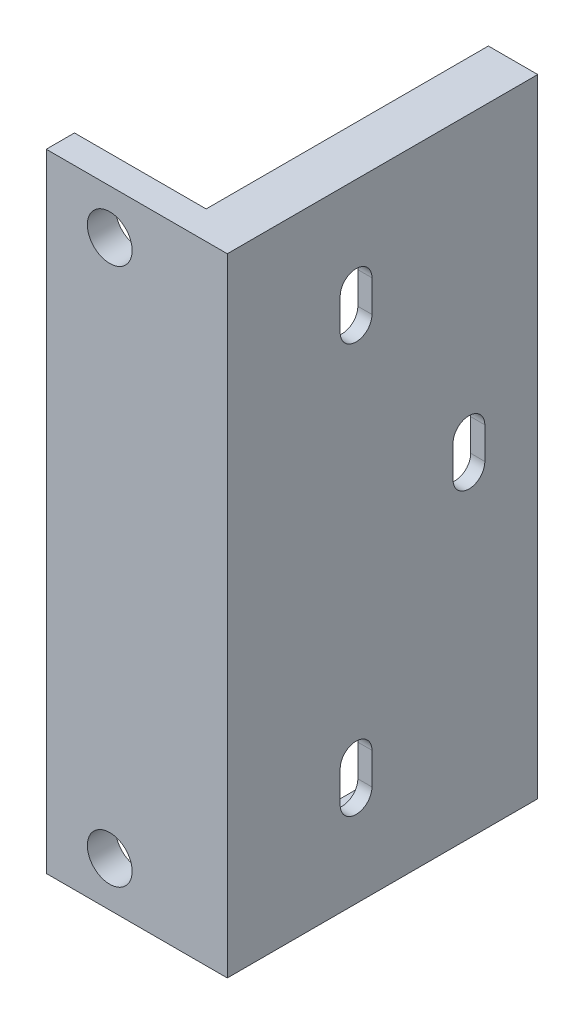
SolidWorks part; units mm, degrees
ref_plane "Front Plane" through (0, 0, 0) normal (0, 0, 1) x (1, 0, 0)
ref_plane "Top Plane" through (0, 0, 0) normal (0, 1, 0) x (1, 0, 0)
ref_plane "Right Plane" through (0, 0, 0) normal (1, 0, 0) x (0, 0, -1)
sketch "Sketch1" plane through (0, 0, 0) normal (0, 0, 1) x (1, 0, 0)
  line L0 (0, 44.45) -> (0, -44.45) construction
  line L1 (-38.7822, -44.45) -> (38.7822, -44.45) construction
  line L2 (-38.7822, -44.45) -> (-38.7822, 44.45) construction
  line L3 (-38.7822, 44.45) -> (38.7822, 44.45) construction
  line L4 (38.7822, -44.45) -> (38.7822, 44.45) construction
  line L5 (-38.7822, -44.45) -> (38.7822, 44.45) construction
  line L6 (-38.7822, 44.45) -> (38.7822, -44.45) construction
  line L7 (0, -44.45) -> (0, 0) construction
  line L8 (0, 0) -> (38.7822, 0) construction
  line L9 (38.7822, 0) -> (-38.7822, 0) construction
  line L10 (-9, 44.45) -> (-9, -44.45)
  line L11 (16.6624, 44.45) -> (16.6624, -44.45) construction
  line L12 (-9, 44.45) -> (38.7822, 44.45) construction
  line L13 (-9, 44.45) -> (-9, -44.45)
  line L14 (-9, -44.45) -> (38.7822, -44.45) construction
  line L15 (38.7822, 44.45) -> (38.7822, -44.45) construction
  line L17 (-9, 44.45) -> (16.6624, 44.45)
  line L18 (-9, 44.45) -> (-9, -44.45)
  line L19 (-9, -44.45) -> (16.6624, -44.45)
  line L20 (16.6624, 44.45) -> (16.6624, -44.45)
  circle A0 centre (0, -38.1) radius 3.175
  circle A1 centre (0, 38.1) radius 3.175
  point P0 (0, 0)
  dimension "D2" = 6.35
  dimension "D1" = 88.9
  dimension "D3" = 38.1
  dimension "D4" = 9
  dimension "D5" = 38.7822
  dimension "D6" = 16.6624
extrude "Boss-Extrude1" add sketch "Sketch1" against normal blind 2 contours L20 L17 L10 L19 A0 A1
sketch "Sketch2" plane through (0, 0, -2) normal (0, 0, -1) x (-1, 0, 0)
  line L0 (9, -44.45) -> (-16.6624, -44.45) construction
  line L1 (-16.6624, 44.45) -> (-14.6624, 44.45)
  line L2 (-16.6624, 44.45) -> (-16.6624, -44.45)
  line L3 (-16.6624, -44.45) -> (-14.6624, -44.45)
  line L4 (-14.6624, 44.45) -> (-14.6624, -44.45)
  dimension "D1" = 2
extrude "Boss-Extrude2" add sketch "Sketch2" along normal blind 40
sketch "Sketch3" plane through (16.6624, 0, 0) normal (1, 0, 0) x (0, 0, -1)
  line L0 (16.25, 44.45) -> (16.25, -44.45) construction
  line L1 (42, 44.45) -> (0, 44.45) construction
  line L2 (42, -44.45) -> (0, -44.45) construction
  line L3 (0, 0) -> (16.25, 0) construction
  line L4 (0, 44.45) -> (0, -44.45) construction
  line L5 (32.25, 44.45) -> (32.25, -44.45) construction
  line L6 (14, -26.75) -> (14, -31.25)
  line L7 (18.5, -26.75) -> (18.5, -31.25)
  line L8 (18.5, 26.75) -> (18.5, 31.25)
  line L9 (14, 26.75) -> (14, 31.25)
  line L10 (30, 5.2) -> (30, 0.7)
  line L11 (34.5, 5.2) -> (34.5, 0.7)
  arc A3 (14, -31.25) -> (18.5, -31.25) centre (16.25, -31.25) ccw
  arc A4 (18.5, -26.75) -> (14, -26.75) centre (16.25, -26.75) ccw
  arc A5 (14, 31.25) -> (18.5, 31.25) centre (16.25, 31.25) cw
  arc A6 (18.5, 26.75) -> (14, 26.75) centre (16.25, 26.75) cw
  arc A7 (30, 0.7) -> (34.5, 0.7) centre (32.25, 0.7) ccw
  arc A8 (34.5, 5.2) -> (30, 5.2) centre (32.25, 5.2) ccw
  dimension "D1" = 4.5
  dimension "D2" = 4.5
  dimension "D5" = 4.5
  dimension "D7" = 4.5
  dimension "D8" = 4.5
  dimension "D9" = 13.2
  dimension "D10" = 4.5
  dimension "D11" = 4.5
  dimension "D6" = 45.15
  dimension "D3" = 16.25
  dimension "D4" = 32.25
extrude "Cut-Extrude1" cut sketch "Sketch3" against normal blind 20
sketch "Sketch7" plane through (0, 0, 0) normal (0, 0, 1) x (1, 0, 0)
  line L0 (-9, 44.45) -> (16.6624, 44.45) construction
  line L1 (16.6624, 44.45) -> (16.6624, -44.45) construction
  line L2 (-9, 44.45) -> (-9, -44.45) construction
  line L3 (-9, -44.45) -> (16.6624, -44.45) construction
  line L4 (-9, 44.45) -> (16.6624, 44.45)
  line L5 (16.6624, 44.45) -> (16.6624, -44.45)
  line L6 (-9, 44.45) -> (-9, -44.45)
  line L7 (-9, -44.45) -> (16.6624, -44.45)
  circle A0 centre (0, -38.1) radius 3.175 construction
  circle A1 centre (0, -38.1) radius 3.175
  circle A2 centre (0, 38.1) radius 3.175 construction
  circle A3 centre (0, 38.1) radius 3.175
sketch "Sketch8" plane through (14.6624, 0, 0) normal (-1, 0, 0) x (0, 0, 1)
  line L0 (-42, 0) -> (-2, 0) construction
  line L1 (-42, -44.45) -> (-42, 44.45) construction
  line L2 (-2, 44.45) -> (-2, -44.45) construction
  line L3 (-2, -44.45) -> (-2, 44.45) construction
  line L4 (-42, -11) -> (-2, -11)
  line L5 (-42, -11) -> (-42, -18)
  line L6 (-42, -18) -> (-2, -18)
  line L7 (-2, -11) -> (-2, -18)
  line L8 (-42, 18) -> (-2, 18)
  line L9 (-2, 11) -> (-2, 18)
  line L10 (-42, 11) -> (-2, 11)
  line L11 (-42, 11) -> (-42, 18)
  line L12 (-42, 37.45) -> (-2, 37.45)
  line L13 (-42, -44.45) -> (-2, -44.45)
  line L14 (-42, -44.45) -> (-42, -37.45)
  line L15 (-42, -37.45) -> (-2, -37.45)
  line L16 (-2, -44.45) -> (-2, -37.45)
  line L17 (-2, 44.45) -> (-2, 37.45)
  line L18 (-42, 44.45) -> (-2, 44.45)
  line L19 (-42, 44.45) -> (-42, 37.45)
  dimension "D1" = 7
  dimension "D2" = 11
  dimension "D3" = 7
extrude "Boss-Extrude6" add sketch "Sketch8" along normal blind 5
sketch "Sketch9" plane through (0, 0, 0) normal (0, 0, 1) x (1, 0, 0)
  line L4 (16.6624, -44.45) -> (16.6624, 44.45)
  line L5 (16.6624, 44.45) -> (-9, 44.45)
  line L6 (-9, 44.45) -> (-9, -44.45)
  line L7 (-9, -44.45) -> (16.6624, -44.45)
  line L8 (16.6624, -44.45) -> (16.6624, 44.45)
  line L9 (16.6624, 44.45) -> (-9, 44.45)
  line L10 (-9, 44.45) -> (-9, -44.45)
  line L11 (-9, -44.45) -> (16.6624, -44.45)
  circle A0 centre (0, -38.1) radius 3.175 construction
  circle A1 centre (0, 38.1) radius 3.175 construction
  circle A2 centre (0, -38.1) radius 3.175
  circle A3 centre (0, 38.1) radius 3.175
  dimension "D1" = 0
extrude "Boss-Extrude8" add sketch "Sketch9" along normal blind 2
extrude "Boss-Extrude5" add sketch "Sketch7" along normal blind 1
